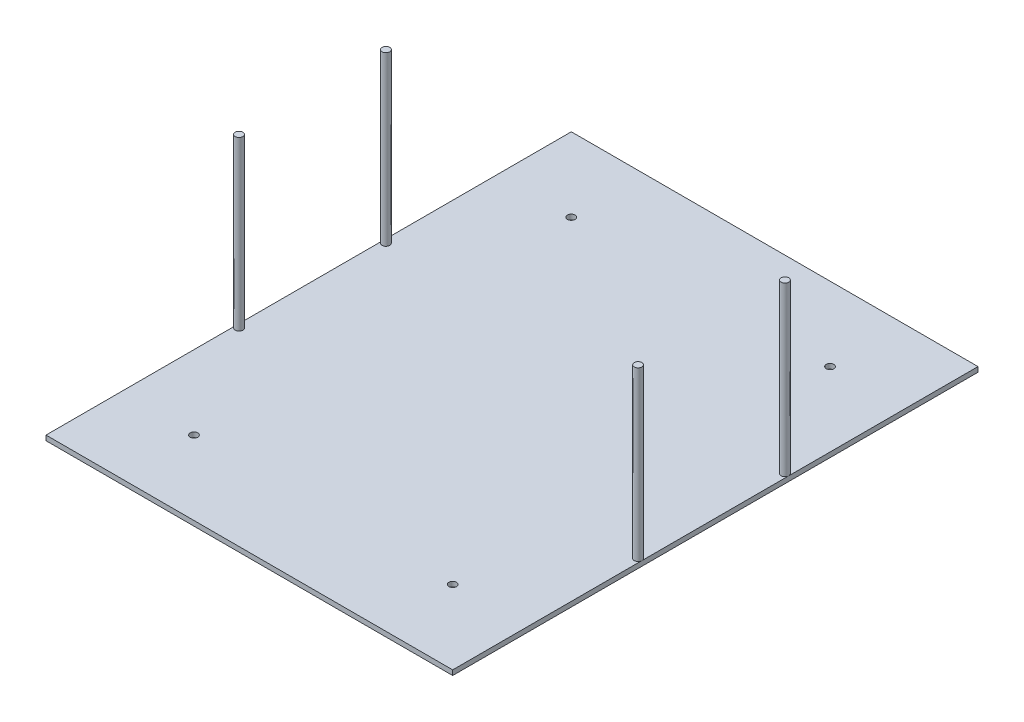
SolidWorks part; units mm, degrees
material "Acrylic (Medium-high impact)"
ref_plane "Front Plane" through (0, 0, 0) normal (0, 0, 1) x (1, 0, 0)
ref_plane "Top Plane" through (0, 0, 0) normal (0, 1, 0) x (1, 0, 0)
ref_plane "Right Plane" through (0, 0, 0) normal (1, 0, 0) x (0, 0, -1)
sketch "Sketch1" plane through (0, 0, 0) normal (0, 1, 0) x (1, 0, 0)
  circle A0 centre (-80.9, 29.78) radius 1.55
  circle A1 centre (-80.9, -29.78) radius 1.55
  circle A2 centre (80.9, 29.78) radius 1.55
  circle A3 centre (80.9, -29.78) radius 1.55
  point P0 (0, 0)
  dimension "D3" = 3.1
  dimension "D1" = 59.56
  dimension "D2" = 161.8
extrude "Boss-Extrude1" add sketch "Sketch1" along normal blind 70
sketch "Sketch2" plane through (0, 0, 0) normal (0, 1, 0) x (1, 0, 0)
  line L5 (-82.45, -106.5) -> (82.45, -106.5)
  line L6 (-82.45, -106.5) -> (-82.45, 106.5)
  line L7 (-82.45, 106.5) -> (82.45, 106.5)
  line L8 (82.45, -106.5) -> (82.45, 106.5)
  line L9 (-82.45, -106.5) -> (82.45, 106.5) construction
  line L10 (-82.45, 106.5) -> (82.45, -106.5) construction
  circle A8 centre (-80.9, 29.78) radius 1.55 construction
  point P0 (0, 0)
  dimension "D1" = 213
extrude "Boss-Extrude2" add sketch "Sketch2" along normal blind 2
sketch "Sketch3" plane through (0, 2, 0) normal (0, 1, 0) x (1, 0, 0)
  line L0 (82.45, 106.5) -> (-82.45, 106.5) construction
  line L2 (-82.45, 106.5) -> (-82.45, 29.78) construction
  line L3 (82.45, 29.78) -> (82.45, 106.5) construction
  line L4 (0, 0) -> (82.45, 0) construction
  line L5 (82.45, -29.78) -> (82.45, 29.78) construction
  circle A0 centre (-52.45, 76.5) radius 1.55
  circle A1 centre (52.45, 76.5) radius 1.55
  circle A2 centre (52.45, -76.5) radius 1.55
  circle A3 centre (-52.45, -76.5) radius 1.55
  dimension "D1" = 3.1
  dimension "D2" = 3.1
  dimension "D3" = 30
  dimension "D4" = 30
  dimension "D5" = 30
  dimension "D6" = 30
extrude "Cut-Extrude1" cut sketch "Sketch3" against normal blind 10
